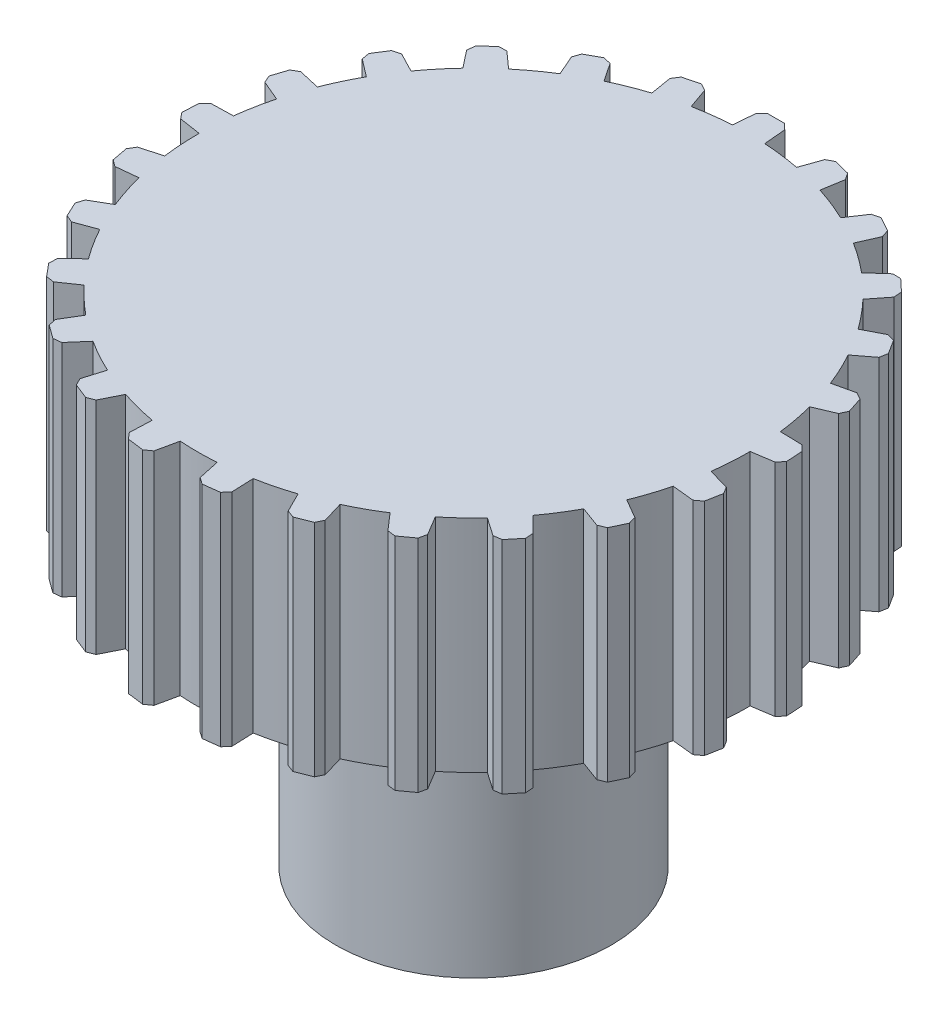
SolidWorks part; units mm, degrees
ref_plane "Front Plane" through (0, 0, 0) normal (0, 0, 1) x (1, 0, 0)
ref_plane "Top Plane" through (0, 0, 0) normal (0, 1, 0) x (1, 0, 0)
ref_plane "Right Plane" through (0, 0, 0) normal (1, 0, 0) x (0, 0, -1)
sketch "Sketch1" plane through (0, 0, 0) normal (0, 1, 0) x (1, 0, 0)
  circle A0 centre (0, 0) radius 12.7
  dimension "D1" = 25.4
extrude "Boss-Extrude1" add sketch "Sketch1" along normal blind 10.16
sketch "Sketch2" plane through (0, 10.16, 0) normal (0, 1, 0) x (1, 0, 0)
  line L0 (-0.7457, 12.6781) -> (-0.6571, 13.6902)
  line L1 (-0.381, 13.9433) -> (0.381, 13.9433)
  line L2 (0.6571, 13.6902) -> (0.7457, 12.6781)
  line L3 (-0.6571, 13.6902) -> (-0.381, 13.9433)
  line L4 (0.381, 13.9433) -> (0.6571, 13.6902)
  circle A0 centre (0, 0) radius 12.7 construction
  circle A2 centre (0, 0) radius 12.7
  arc A3 (0.7457, 12.6781) -> (-0.7457, 12.6781) centre (0, 0) ccw
  point P1 (-0.635, 13.9433)
  point P5 (0.635, 13.9433)
  point P8 (0, 13.9433)
  point P13 (0, 12.7)
  dimension "D1" = 95
  dimension "D2" = 95
  dimension "D3" = 1.27
  dimension "D4" = 1.27
  dimension "D5" = 0
extrude "Boss-Extrude2" add sketch "Sketch2" against normal up to surface (10.16 mm away) up to face at (0, 0, 12.7)
pattern_circular "CirPattern1" count 25 over 360 about axis through (0, 0, 0) along (0, 1, 0) of "Boss-Extrude2"
sketch "Sketch3" plane through (0, 0, 0) normal (0, -1, 0) x (1, 0, 0)
  circle A0 centre (0, 0) radius 6.35
  dimension "D1" = 12.7
extrude "Boss-Extrude3" add sketch "Sketch3" along normal blind 12.7
sketch "Sketch4" plane through (0, -12.7, 0) normal (0, -1, 0) x (1, 0, 0)
  line L0 (-1.4256, 0.9525) -> (1.4256, 0.9525)
  arc A0 (-1.4256, 0.9525) -> (1.4256, 0.9525) centre (0, 0) ccw
  dimension "D1" = 3.429
  dimension "D2" = 2.667
extrude "Cut-Extrude1" cut sketch "Sketch4" against normal blind 6.35
fillet "Fillet1" radius 1.27 1 edges at (0, 0, 6.35)
